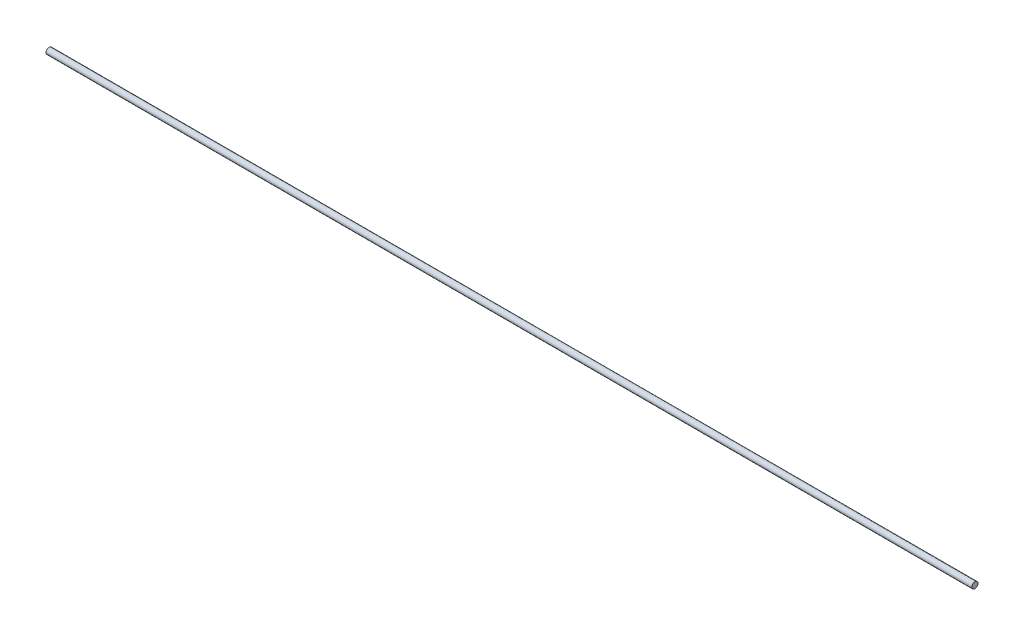
SolidWorks part; units mm, degrees
ref_plane "Front Plane" through (0, 0, 0) normal (0, 0, 1) x (1, 0, 0)
ref_plane "Top Plane" through (0, 0, 0) normal (0, 1, 0) x (1, 0, 0)
ref_plane "Right Plane" through (0, 0, 0) normal (1, 0, 0) x (0, 0, -1)
sketch "Sketch1" plane through (0, 0, 0) normal (1, 0, 0) x (0, 0, -1)
  circle A0 centre (0, 0) radius 0.5
  dimension "D1" = 1
extrude "Boss-Extrude1" add sketch "Sketch1" along normal blind 150 contours A0
sketch "Sketch2" plane through (150, 0, 0) normal (1, 0, 0) x (0, 0, -1)
  point P0 (0, 0)
sketch "Sketch3" plane through (0, 0, 0) normal (-1, 0, 0) x (0, 0, 1)
  point P0 (0, 0)
